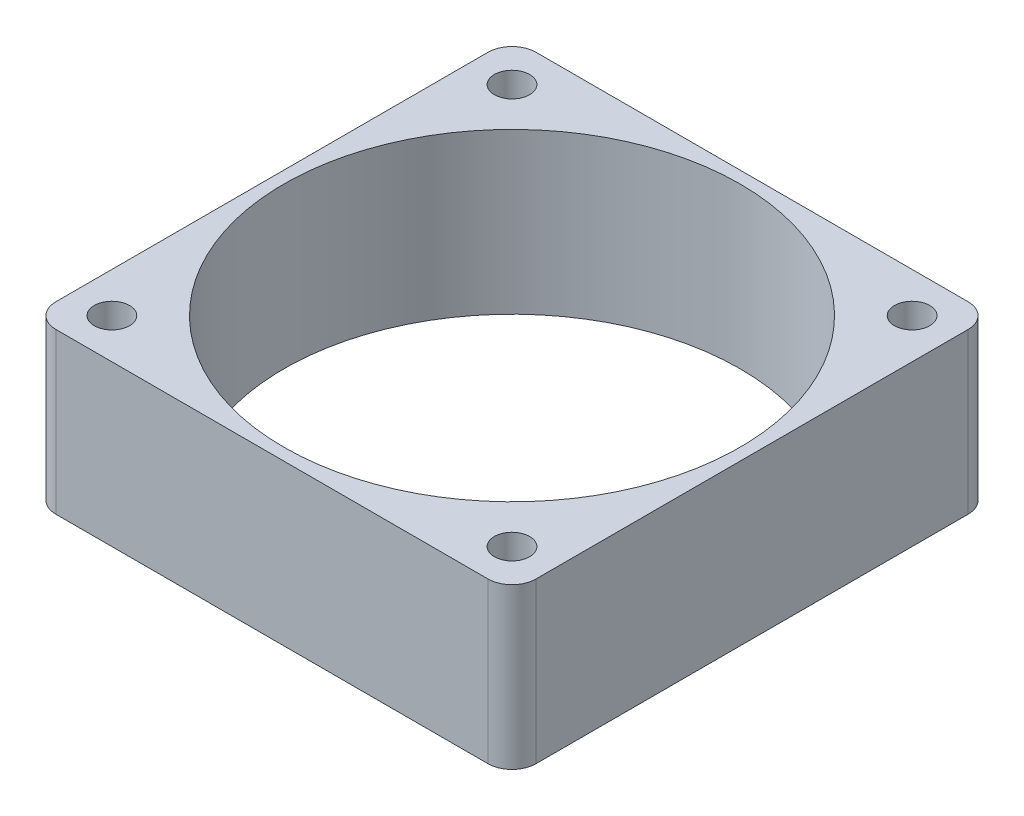
SolidWorks part; units mm, degrees
ref_plane "Front Plane" through (0, 0, 0) normal (0, 0, 1) x (1, 0, 0)
ref_plane "Top Plane" through (0, 0, 0) normal (0, 1, 0) x (1, 0, 0)
ref_plane "Right Plane" through (0, 0, 0) normal (1, 0, 0) x (0, 0, -1)
sketch "Sketch1" plane through (0, 0, 0) normal (0, 1, 0) x (1, 0, 0)
  line L1 (0, 0) -> (60, 0)
  line L2 (0, 0) -> (0, -60)
  line L3 (0, -60) -> (60, -60)
  line L4 (60, 0) -> (60, -60)
  circle A0 centre (5, -55) radius 2.2
  circle A1 centre (55, -55) radius 2.2
  circle A2 centre (55, -5) radius 2.2
  circle A3 centre (5, -5) radius 2.2
  circle A4 centre (30, -30) radius 28.5
  dimension "D3" = 4.4
  dimension "D8" = 57
  dimension "D1" = 60
  dimension "D2" = 60
  dimension "D4" = 5
  dimension "D5" = 5
  dimension "D6" = 2
  dimension "D7" = 2
extrude "Boss-Extrude1" add sketch "Sketch1" along normal blind 20
fillet "Fillet1" radius 3 4 edges at (0, 10, 0) (60, 10, 0) (60, 10, 60) (0, 10, 60)
